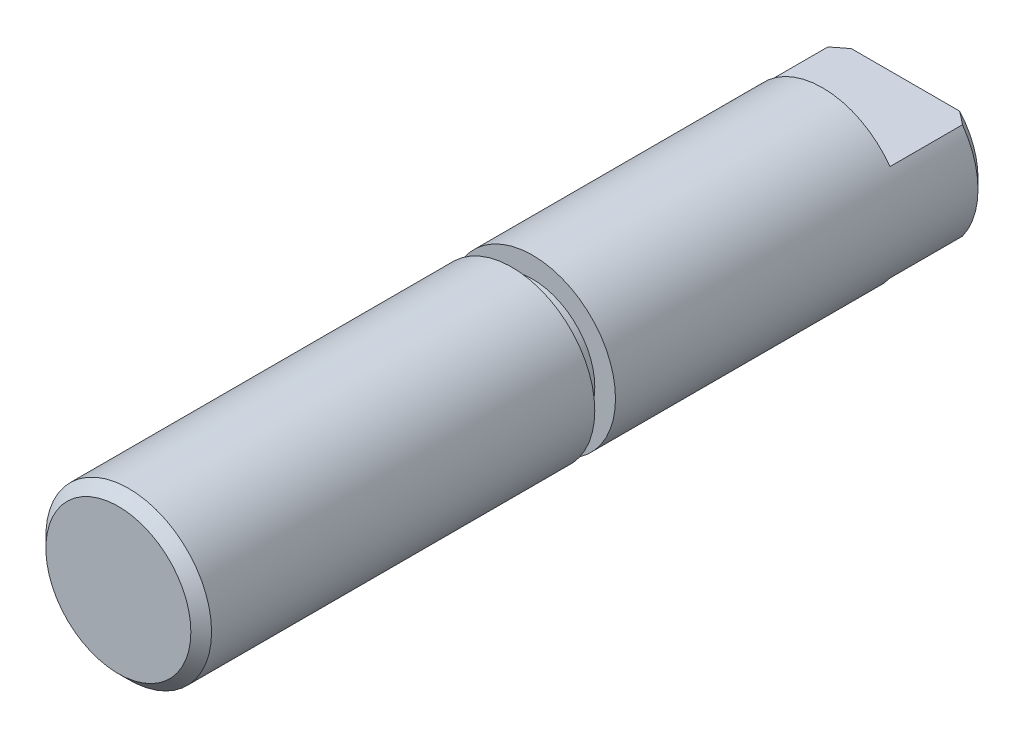
SolidWorks part; units mm, degrees
ref_plane "Face" through (0, 0, 0) normal (0, 0, 1) x (1, 0, 0)
ref_plane "Dessus" through (0, 0, 0) normal (0, 1, 0) x (1, 0, 0)
ref_plane "Droite" through (0, 0, 0) normal (1, 0, 0) x (0, 0, -1)
sketch "Esquisse1" plane through (0, 0, 0) normal (0, 0, 1) x (1, 0, 0)
  circle A0 centre (0, 0) radius 4
  dimension "D1" = 8
extrude "Base-Extrusion" add sketch "Esquisse1" along normal blind 38
chamfer "Chanfrein1" distance 0.5 angle 45
ref_plane "Plan1" through (0, 0, 19) normal (0, 0, 1) x (1, 0, 0)
sketch "Esquisse2" plane through (0, 0, 19) normal (0, 0, 1) x (1, 0, 0)
  circle A0 centre (0, 0) radius 3
  dimension "D1" = 6
extrude "Enlèv. mat.-Extru.1" cut sketch "Esquisse2" against normal blind 1 flip side to cut
sketch "Esquisse3" plane through (0, 0, 0) normal (0, 0, -1) x (-1, 0, 0)
  line L0 (-3.251, 2.3305) -> (3.251, 2.3305)
  line L1 (0, 0) -> (6.8269, 0) construction
  line L2 (-3.251, -2.3305) -> (3.251, -2.3305)
  circle A0 centre (0, 0) radius 4 construction
  arc A1 (-3.251, 2.3305) -> (-3.251, -2.3305) centre (0, 0) ccw
  arc A2 (3.251, -2.3305) -> (3.251, 2.3305) centre (0, 0) ccw
extrude "Enlèv. mat.-Extru.2" cut sketch "Esquisse3" against normal blind 4 flip side to cut
